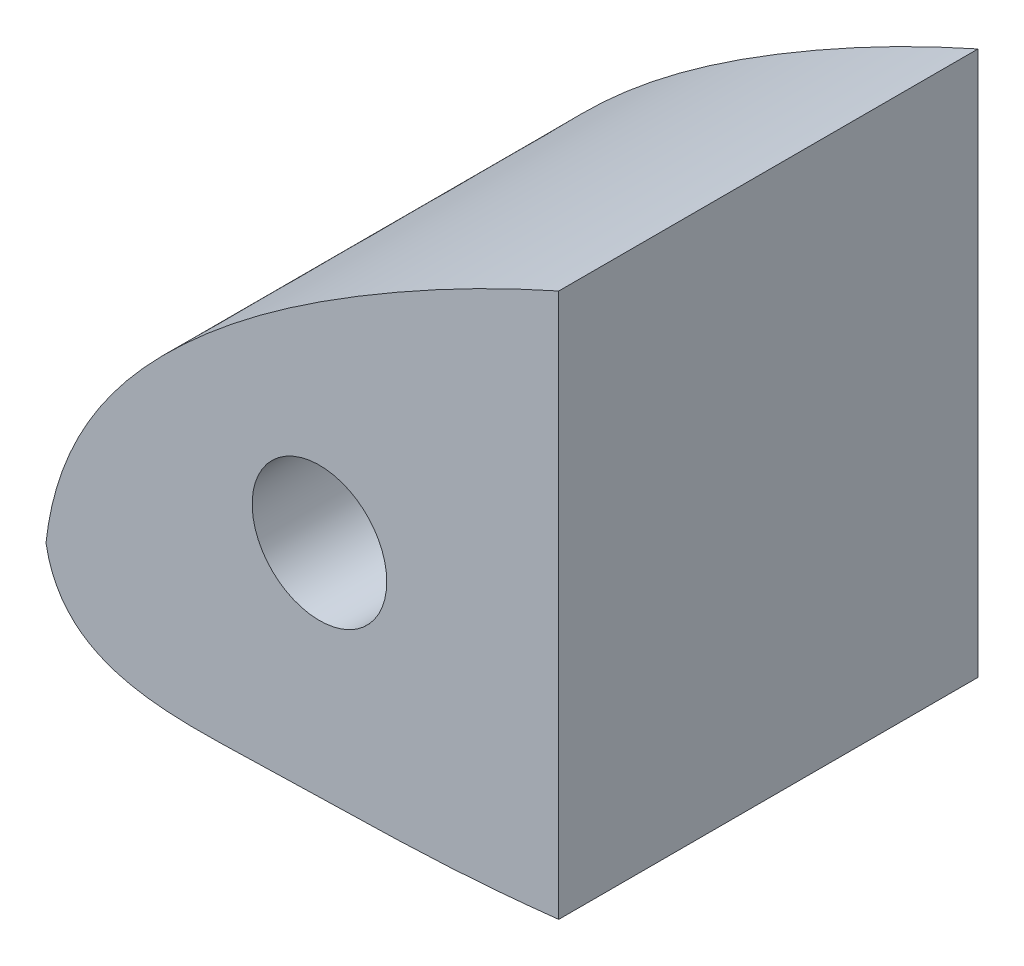
SolidWorks part; units mm, degrees
ref_plane "Front Plane" through (0, 0, 0) normal (0, 0, 1) x (1, 0, 0)
ref_plane "Top Plane" through (0, 0, 0) normal (0, 1, 0) x (1, 0, 0)
ref_plane "Right Plane" through (0, 0, 0) normal (1, 0, 0) x (0, 0, -1)
sketch "Sketch1" plane through (0, 0, 0) normal (0, 0, 1) x (1, 0, 0)
  spline S0 degree 3 poles (0.0006, 0.0001) (0.8106, 7.3592) (8.6491, 17.8566) (26.2867, 29.9752) (52.1111, 42.0692) (89.5976, 49.2908) (131.4008, 47.8848) (173.2567, 40.0411) (217.9611, 29.613) (256.9521, 19.5289) (290.3598, 8.711) (301.2732, 4.3828) (314.8169, -0.5162) (309.8463, 0.0001) knots 0 0 0 0 0.060864 0.113688 0.188609 0.312909 0.448482 0.557612 0.691544 0.852438 0.929756 0.976058 1 1 1 1
  spline S1 degree 3 poles (309.8463, 0.0001) (303.9568, 1.471) (293.9895, 2.094) (276.264, 4.5144) (260.8463, 5.4274) (235.8588, 7.8703) (205.1014, 8.8381) (157.7186, 9.0307) (110.4973, 6.1815) (66.5062, -0.5867) (36.4547, -6.0985) (15.3166, -6.1891) (1.2307, -6.9241) (0.0006, 0.0001) knots 0 0 0 0 0.057787 0.095275 0.171021 0.205339 0.335319 0.464904 0.658702 0.785512 0.893517 0.943092 1 1 1 1
extrude "Boss-Extrude1" add sketch "Sketch1" along normal blind 31.1531
sketch "Sketch2" plane through (0, 0, 31.1531) normal (0, 0, 1) x (1, 0, 0)
  circle A0 centre (20.32, 10.16) radius 5
  circle A1 centre (227.2963, 19.0501) radius 3.175
  dimension "D2" = 10
  dimension "D3" = 6.35
  dimension "D6" = 20.32
  dimension "D1" = 82.55
  dimension "D4" = 19.05
  dimension "D5" = 10.16
extrude "Cut-Extrude1" cut sketch "Sketch2" against normal through all
sketch "Sketch3" plane through (0, 0, 31.1531) normal (0, 0, 1) x (1, 0, 0)
  line L1 (38.1, 71.718) -> (331.2889, 71.718)
  line L2 (38.1, 71.718) -> (38.1, -66.2532)
  line L3 (38.1, -66.2532) -> (331.2889, -66.2532)
  line L4 (331.2889, 71.718) -> (331.2889, -66.2532)
  dimension "D1" = 38.1
extrude "Cut-Extrude2" cut sketch "Sketch3" against normal through all
